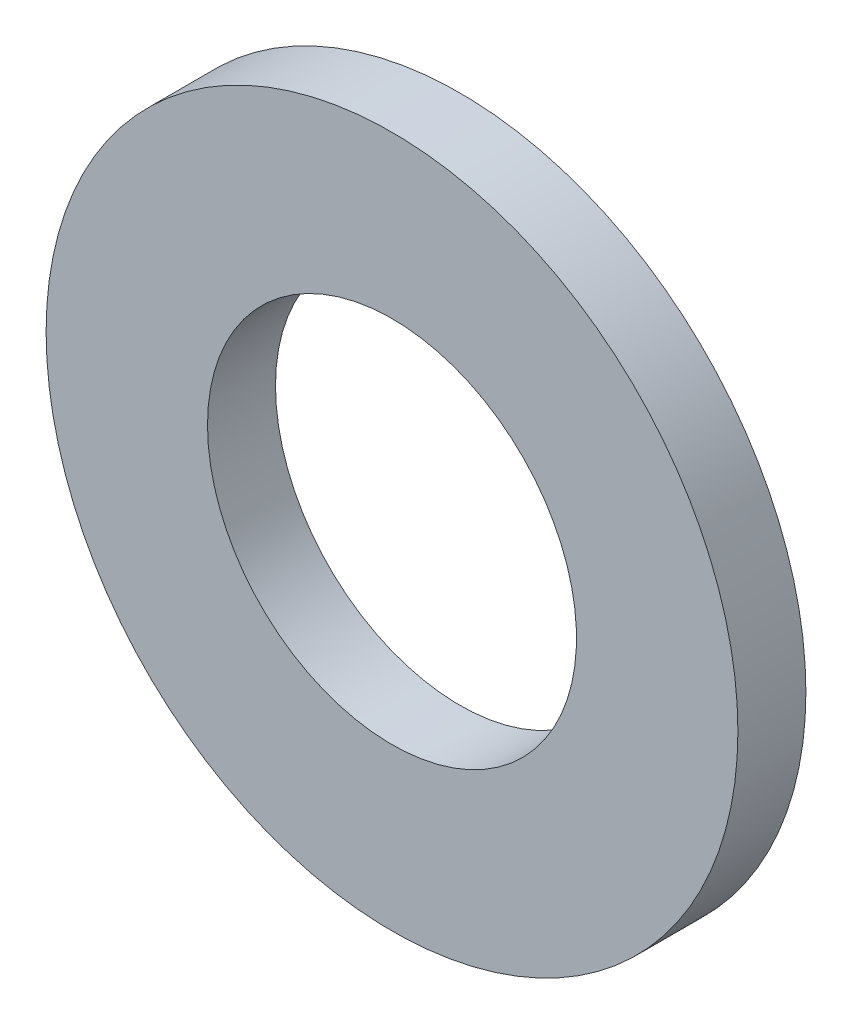
SolidWorks part; units mm, degrees
ref_plane "Front Plane" through (0, 0, 0) normal (0, 0, 1) x (1, 0, 0)
ref_plane "Top Plane" through (0, 0, 0) normal (0, 1, 0) x (1, 0, 0)
ref_plane "Right Plane" through (0, 0, 0) normal (1, 0, 0) x (0, 0, -1)
sketch "Sketch1" plane through (0, 0, 0) normal (0, 0, 1) x (1, 0, 0)
  circle A0 centre (0, 0) radius 6.35
  circle A1 centre (0, 0) radius 11.905
  dimension "D1" = 12.7
  dimension "D2" = 23.81
extrude "Boss-Extrude1" add sketch "Sketch1" along normal blind 2.34
